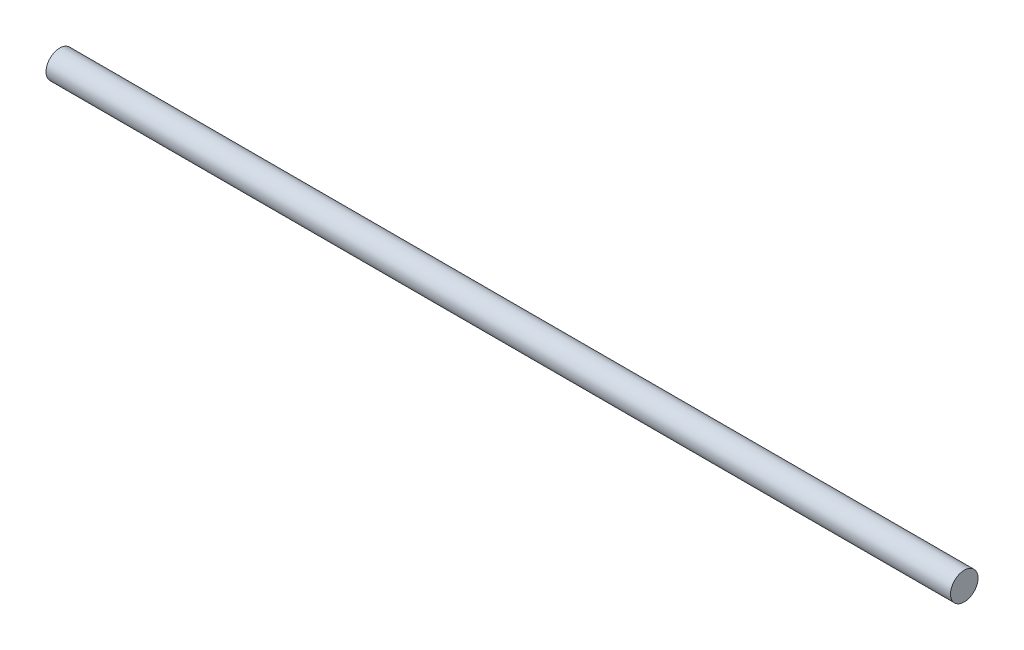
SolidWorks part; units mm, degrees
material "1.0503 (C45)"
ref_plane "Plan de face" through (0, 0, 0) normal (0, 0, 1) x (1, 0, 0)
ref_plane "Plan de dessus" through (0, 0, 0) normal (0, 1, 0) x (1, 0, 0)
ref_plane "Plan de droite" through (0, 0, 0) normal (1, 0, 0) x (0, 0, -1)
sketch "Esquisse1" plane through (0, 0, 0) normal (0, 1, 0) x (1, 0, 0)
  line L0 (0, 0) -> (143.2922, 0) construction
  line L2 (0, 0) -> (460, 0)
  line L3 (0, 0) -> (0, 7)
  line L4 (0, 7) -> (460, 7)
  line L5 (460, 0) -> (460, 7)
  dimension "D1" = 14
  dimension "D2" = 460
revolve "Révolution1" add sketch "Esquisse1" angle 360 about L0
